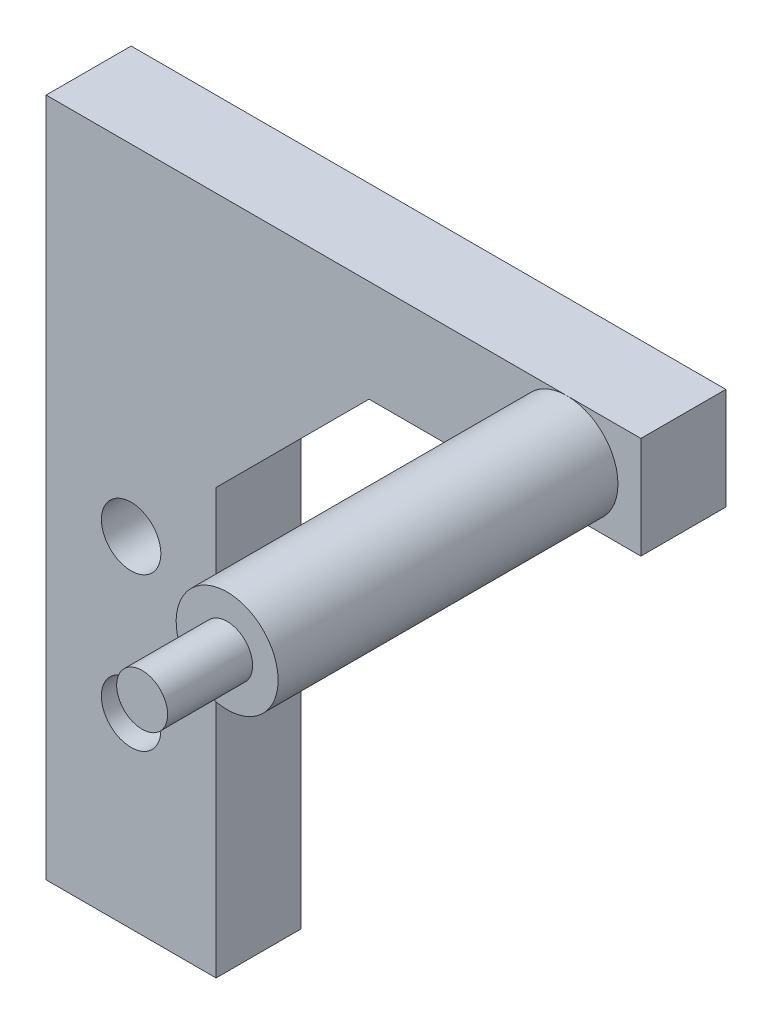
SolidWorks part; units mm, degrees
ref_plane "Ebene vorne" through (0, 0, 0) normal (0, 0, 1) x (1, 0, 0)
ref_plane "Ebene oben" through (0, 0, 0) normal (0, 1, 0) x (1, 0, 0)
ref_plane "Ebene rechts" through (0, 0, 0) normal (1, 0, 0) x (0, 0, -1)
sketch "Skizze2" plane through (0, 0, 0) normal (0, 0, 1) x (1, 0, 0)
  line L1 (-5, -20) -> (5, -20)
  line L2 (-5, -20) -> (-5, 20)
  line L3 (-5, 20) -> (5, 20)
  line L4 (5, -20) -> (5, 20)
  line L5 (-5, -20) -> (5, 20) construction
  line L6 (-5, 20) -> (5, -20) construction
  point P0 (0, 0)
  dimension "D1" = 10
  dimension "D2" = 40
extrude "Aufsatz-Linear austragen1" add sketch "Skizze2" along normal blind 5
sketch "Skizze4" plane through (0, 0, 5) normal (0, 0, 1) x (1, 0, 0)
  circle A0 centre (0, 0) radius 1.75
  circle A1 centre (0, -9) radius 1.75
  dimension "D3" = 3.5
  dimension "D4" = 3.5
  dimension "D1" = 9
extrude "Schnitt-Linear austragen1" cut sketch "Skizze4" against normal blind 5
sketch "Skizze5" plane through (0, 0, 0) normal (0, 0, -1) x (-1, 0, 0)
  line L1 (-2.5, 17.5) -> (2.5, 17.5)
  line L2 (-2.5, 17.5) -> (-2.5, 12.5)
  line L3 (-2.5, 12.5) -> (2.5, 12.5)
  line L4 (2.5, 17.5) -> (2.5, 12.5)
  line L5 (-2.5, 17.5) -> (2.5, 12.5) construction
  line L6 (-2.5, 12.5) -> (2.5, 17.5) construction
  circle A0 centre (0, 0) radius 1.75 construction
  point P4 (0, 15)
  dimension "D1" = 15
  dimension "D2" = 5
  dimension "D3" = 5
extrude "Schnitt-Linear austragen2" cut sketch "Skizze5" against normal blind 2
sketch "Skizze6" plane through (0, 0, 5) normal (0, 0, 1) x (1, 0, 0)
  line L1 (5, 20) -> (30, 20)
  line L2 (5, 20) -> (5, 14)
  line L3 (5, 14) -> (30, 14)
  line L4 (30, 20) -> (30, 14)
  line L5 (5, 20) -> (30, 14) construction
  line L6 (5, 14) -> (30, 20) construction
  point P4 (17.5, 17)
  dimension "D3" = 17
  dimension "D1" = 6
  dimension "D2" = 25
extrude "Aufsatz-Linear austragen3" add sketch "Skizze6" against normal blind 5
sketch "Skizze7" plane through (0, 0, 5) normal (0, 0, 1) x (1, 0, 0)
  line L0 (30, 20) -> (-5, 20) construction
  circle A0 centre (25.65, 17) radius 3
  dimension "D3" = 6
  dimension "D1" = 20.65
  dimension "D2" = 3
extrude "Aufsatz-Linear austragen4" add sketch "Skizze7" along normal blind 20
sketch "Skizze8" plane through (0, 0, 25) normal (0, 0, 1) x (1, 0, 0)
  circle A0 centre (25.65, 17) radius 1.5
  dimension "D1" = 3
extrude "Aufsatz-Linear austragen5" add sketch "Skizze8" along normal blind 5
sketch "Skizze9" plane through (0, 0, 5) normal (0, 0, 1) x (1, 0, 0)
  line L0 (5, 5) -> (5, 10.6569)
  line L1 (5, 5) -> (14.3431, 14.3431)
  line L2 (5, 10.6569) -> (14.3431, 20)
  line L3 (14.3431, 14.3431) -> (14.3431, 20)
  line L4 (5, -20) -> (5, 14) construction
  line L5 (25.65, 20) -> (-5, 20) construction
  line L6 (14.3431, 20) -> (5, 10.6569)
  line L7 (14.3431, 20) -> (9.8569, 19.9447)
  line L8 (5, 10.6569) -> (0.5138, 10.6016)
  line L9 (9.8569, 19.9447) -> (0.5138, 10.6016)
  line M7 (5, -20) -> (5, 14)
  line M8 (5, 14) -> (25.65, 14)
  dimension "D1" = 45
  dimension "D2" = 4
  dimension "D3" = 5
extrude "Aufsatz-Linear austragen6" add sketch "Skizze9" against normal blind 5 contours L2 M7 M8 | L2 L1 M7 M8
